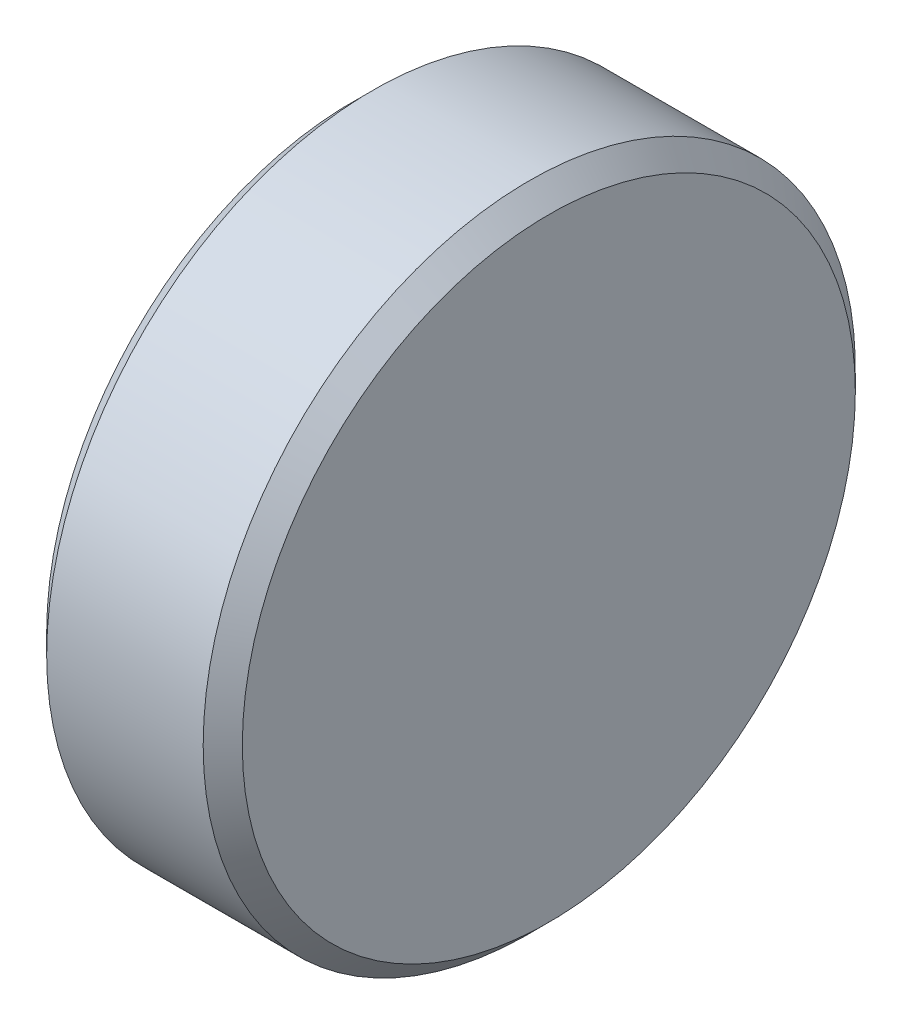
SolidWorks part; units mm, degrees
material "PLA"
ref_plane "Front Plane" through (0, 0, 0) normal (0, 0, 1) x (1, 0, 0)
ref_plane "Top Plane" through (0, 0, 0) normal (0, 1, 0) x (1, 0, 0)
ref_plane "Right Plane" through (0, 0, 0) normal (1, 0, 0) x (0, 0, -1)
sketch "Sketch1" plane through (0, 0, 0) normal (1, 0, 0) x (0, 0, -1)
  circle A0 centre (0, 0) radius 31.75
  dimension "D1" = 63.5
extrude "Boss-Extrude1" add sketch "Sketch1" along normal blind 19.05
sketch "Sketch2" plane through (0, 0, 0) normal (-1, 0, 0) x (0, 0, 1)
  circle A0 centre (0, 0) radius 2.9845
  dimension "D1" = 5.969
extrude "Cut-Extrude1" cut sketch "Sketch2" against normal blind 12.7
chamfer "Chamfer1" distance 1.905 angle 45 2 edges at (19.05, 0, -31.75) (0, 0, -31.75)
